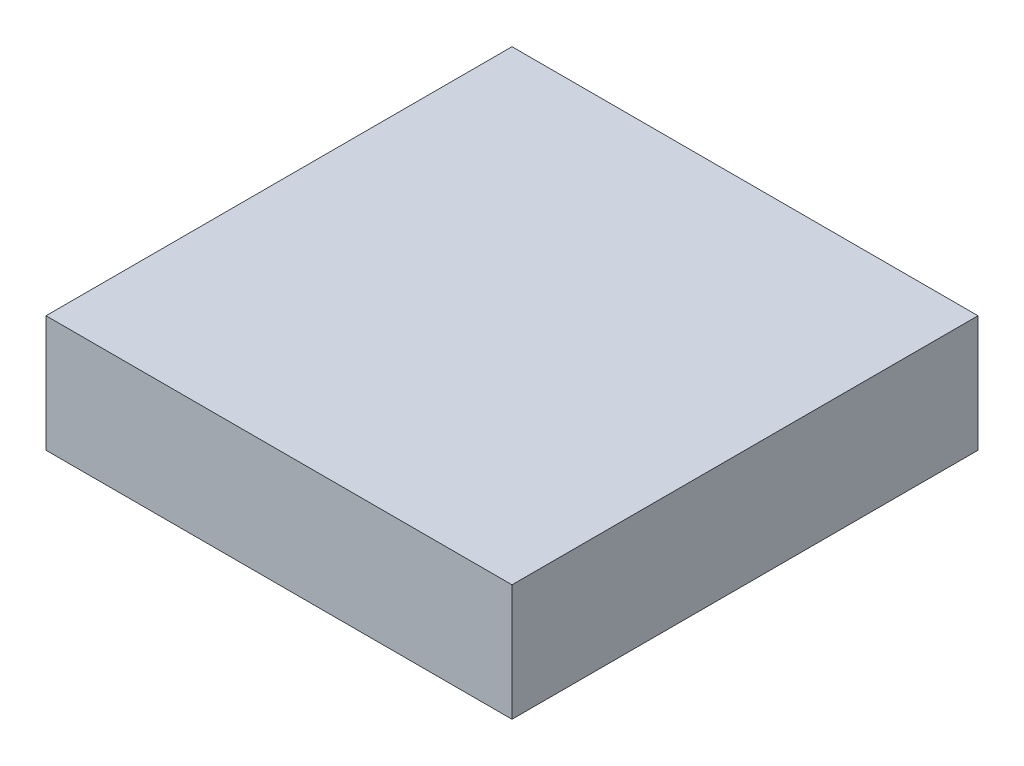
SolidWorks part; units mm, degrees
ref_plane "Front Plane" through (0, 0, 0) normal (0, 0, 1) x (1, 0, 0)
ref_plane "Top Plane" through (0, 0, 0) normal (0, 1, 0) x (1, 0, 0)
ref_plane "Right Plane" through (0, 0, 0) normal (1, 0, 0) x (0, 0, -1)
sketch "Sketch1" plane through (0, 0, 0) normal (0, 1, 0) x (1, 0, 0)
  line L1 (-28.5448, -11.4905) -> (-3.1448, -11.4905)
  line L2 (-28.5448, -11.4905) -> (-28.5448, 13.9095)
  line L3 (-28.5448, 13.9095) -> (-3.1448, 13.9095)
  line L4 (-3.1448, -11.4905) -> (-3.1448, 13.9095)
  dimension "D1" = 25.4
  dimension "D2" = 25.4
extrude "Boss-Extrude1" add sketch "Sketch1" along normal blind 6.35
